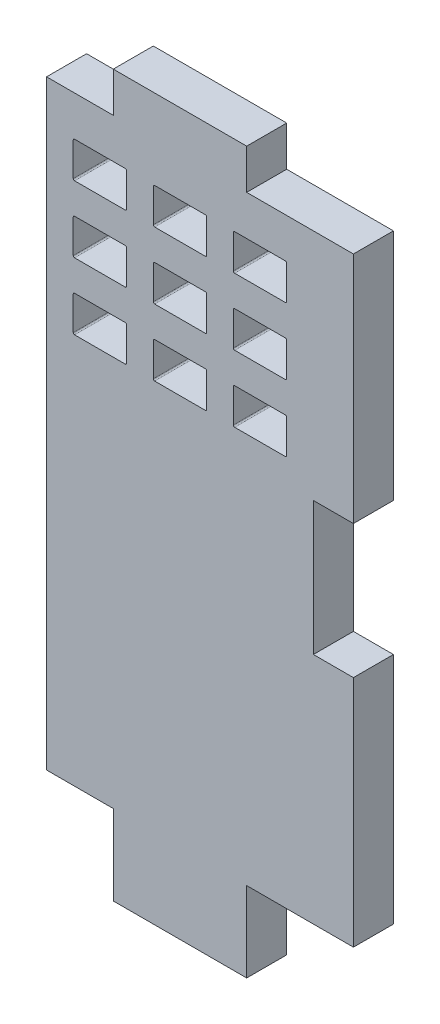
SolidWorks part; units mm, degrees
ref_plane "Front Plane" through (0, 0, 0) normal (0, 0, 1) x (1, 0, 0)
ref_plane "Top Plane" through (0, 0, 0) normal (0, 1, 0) x (1, 0, 0)
ref_plane "Right Plane" through (0, 0, 0) normal (1, 0, 0) x (0, 0, -1)
sketch "Sketch1" plane through (0, 0, 0) normal (0, 0, 1) x (1, 0, 0)
  line L0 (0, 0) -> (0, 45)
  line L1 (0, 45) -> (5, 45)
  line L2 (5, 45) -> (5, 48)
  line L3 (5, 48) -> (15, 48)
  line L4 (15, 48) -> (15, 45)
  line L5 (15, 45) -> (23, 45)
  line L6 (23, 45) -> (23, 27.5)
  line L7 (23, 27.5) -> (20, 27.5)
  line L8 (20, 27.5) -> (20, 17.5)
  line L9 (20, 17.5) -> (23, 17.5)
  line L10 (23, 17.5) -> (23, 0)
  line L11 (23, 0) -> (15, 0)
  line L12 (15, 0) -> (15, -6)
  line L13 (15, -6) -> (5, -6)
  line L14 (5, -6) -> (5, 0)
  line L15 (5, 0) -> (0, 0)
  dimension "D1" = 10
  dimension "D2" = 3
  dimension "D3" = 23
  dimension "D4" = 10
  dimension "D5" = 5
  dimension "D6" = 45
  dimension "D7" = 3
  dimension "D8" = 6
extrude "Boss-Extrude1" add sketch "Sketch1" along normal blind 3
sketch "Sketch2" plane through (0, 0, 3) normal (0, 0, 1) x (1, 0, 0)
  line L0 (5, 45) -> (0, 45) construction
  line L1 (2.1, 42) -> (5.9, 42)
  line L2 (2, 41.9) -> (2, 39.4)
  line L3 (2.1, 39.3) -> (5.9, 39.3)
  line L4 (6, 41.9) -> (6, 39.4)
  line L5 (0, 45) -> (0, 0) construction
  line L6 (8.1, 42) -> (11.9, 42)
  line L7 (8, 41.9) -> (8, 39.4)
  line L8 (8.1, 39.3) -> (11.9, 39.3)
  line L9 (12, 41.9) -> (12, 39.4)
  line L10 (14.1, 42) -> (17.9, 42)
  line L11 (14, 41.9) -> (14, 39.4)
  line L12 (14.1, 39.3) -> (17.9, 39.3)
  line L13 (18, 41.9) -> (18, 39.4)
  line L14 (8.1, 37) -> (11.9, 37)
  line L15 (8, 36.9) -> (8, 34.4)
  line L16 (8.1, 34.3) -> (11.9, 34.3)
  line L17 (12, 36.9) -> (12, 34.4)
  line L18 (14.1, 37) -> (17.9, 37)
  line L19 (14, 36.9) -> (14, 34.4)
  line L20 (14.1, 34.3) -> (17.9, 34.3)
  line L21 (18, 36.9) -> (18, 34.4)
  line L22 (8.1, 32) -> (11.9, 32)
  line L23 (8, 31.9) -> (8, 29.4)
  line L24 (8.1, 29.3) -> (11.9, 29.3)
  line L25 (12, 31.9) -> (12, 29.4)
  line L26 (14.1, 32) -> (17.9, 32)
  line L27 (14, 31.9) -> (14, 29.4)
  line L28 (14.1, 29.3) -> (17.9, 29.3)
  line L29 (18, 31.9) -> (18, 29.4)
  line L30 (2.1, 37) -> (5.9, 37)
  line L31 (2, 36.9) -> (2, 34.4)
  line L32 (2.1, 34.3) -> (5.9, 34.3)
  line L33 (6, 36.9) -> (6, 34.4)
  line L34 (2.1, 32) -> (5.9, 32)
  line L35 (2, 31.9) -> (2, 29.4)
  line L36 (2.1, 29.3) -> (5.9, 29.3)
  line L37 (6, 31.9) -> (6, 29.4)
  line L38 (23, 45) -> (15, 45) construction
  arc A0 (2, 39.4) -> (2.1, 39.3) centre (2.1, 39.4) ccw
  arc A1 (5.9, 39.3) -> (6, 39.4) centre (5.9, 39.4) ccw
  arc A2 (5.9, 42) -> (6, 41.9) centre (5.9, 41.9) cw
  arc A3 (2.1, 42) -> (2, 41.9) centre (2.1, 41.9) ccw
  arc A4 (11.9, 42) -> (12, 41.9) centre (11.9, 41.9) cw
  arc A5 (8.1, 42) -> (8, 41.9) centre (8.1, 41.9) ccw
  arc A6 (11.9, 39.3) -> (12, 39.4) centre (11.9, 39.4) ccw
  arc A7 (8, 39.4) -> (8.1, 39.3) centre (8.1, 39.4) ccw
  arc A8 (17.9, 42) -> (18, 41.9) centre (17.9, 41.9) cw
  arc A9 (14.1, 42) -> (14, 41.9) centre (14.1, 41.9) ccw
  arc A10 (17.9, 39.3) -> (18, 39.4) centre (17.9, 39.4) ccw
  arc A11 (14, 39.4) -> (14.1, 39.3) centre (14.1, 39.4) ccw
  arc A12 (11.9, 37) -> (12, 36.9) centre (11.9, 36.9) cw
  arc A13 (8.1, 37) -> (8, 36.9) centre (8.1, 36.9) ccw
  arc A14 (11.9, 34.3) -> (12, 34.4) centre (11.9, 34.4) ccw
  arc A15 (8, 34.4) -> (8.1, 34.3) centre (8.1, 34.4) ccw
  arc A16 (17.9, 37) -> (18, 36.9) centre (17.9, 36.9) cw
  arc A17 (14.1, 37) -> (14, 36.9) centre (14.1, 36.9) ccw
  arc A18 (17.9, 34.3) -> (18, 34.4) centre (17.9, 34.4) ccw
  arc A19 (14, 34.4) -> (14.1, 34.3) centre (14.1, 34.4) ccw
  arc A20 (11.9, 32) -> (12, 31.9) centre (11.9, 31.9) cw
  arc A21 (8.1, 32) -> (8, 31.9) centre (8.1, 31.9) ccw
  arc A22 (11.9, 29.3) -> (12, 29.4) centre (11.9, 29.4) ccw
  arc A23 (8, 29.4) -> (8.1, 29.3) centre (8.1, 29.4) ccw
  arc A24 (17.9, 32) -> (18, 31.9) centre (17.9, 31.9) cw
  arc A25 (14.1, 32) -> (14, 31.9) centre (14.1, 31.9) ccw
  arc A26 (17.9, 29.3) -> (18, 29.4) centre (17.9, 29.4) ccw
  arc A27 (14, 29.4) -> (14.1, 29.3) centre (14.1, 29.4) ccw
  arc A28 (5.9, 37) -> (6, 36.9) centre (5.9, 36.9) cw
  arc A29 (2.1, 37) -> (2, 36.9) centre (2.1, 36.9) ccw
  arc A30 (5.9, 34.3) -> (6, 34.4) centre (5.9, 34.4) ccw
  arc A31 (2, 34.4) -> (2.1, 34.3) centre (2.1, 34.4) ccw
  arc A32 (5.9, 32) -> (6, 31.9) centre (5.9, 31.9) cw
  arc A33 (2.1, 32) -> (2, 31.9) centre (2.1, 31.9) ccw
  arc A34 (5.9, 29.3) -> (6, 29.4) centre (5.9, 29.4) ccw
  arc A35 (2, 29.4) -> (2.1, 29.3) centre (2.1, 29.4) ccw
  point P12 (6, 39.3)
  point P15 (6, 42)
  point P18 (2, 42)
  dimension "D5" = 0.1
  dimension "D1" = 4
  dimension "D2" = 2.7
  dimension "D3" = 3
  dimension "D4" = 2
  dimension "D8" = 8
  dimension "D9" = 3
  dimension "D10" = 2.3
  dimension "D6" = 3
  dimension "D7" = 3
extrude "Cut-Extrude1" cut sketch "Sketch2" against normal through all
